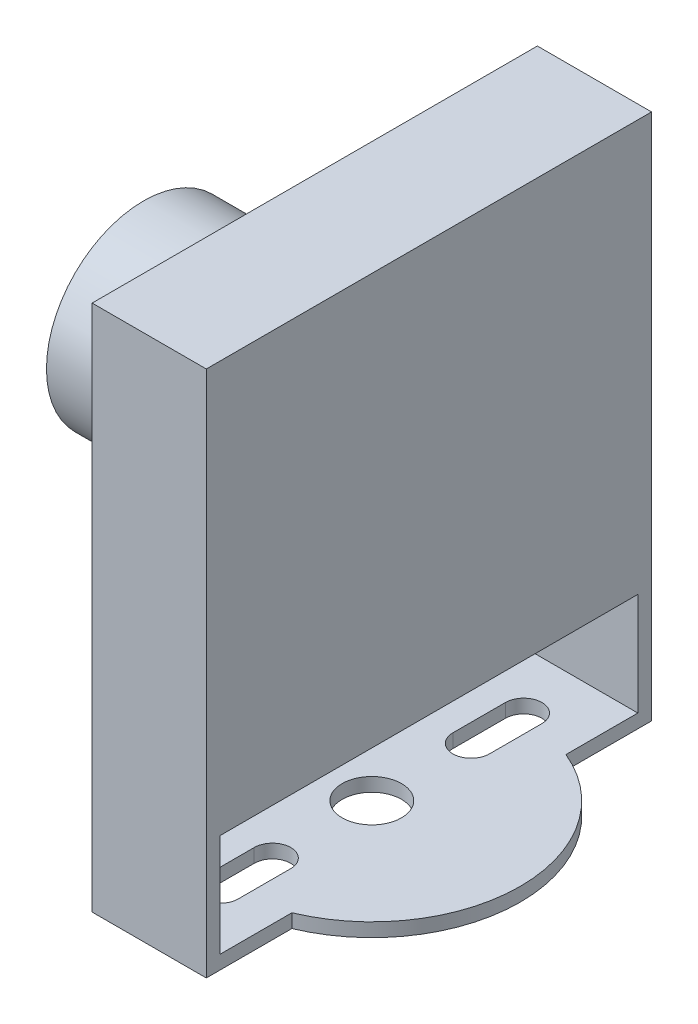
SolidWorks part; units mm, degrees
ref_plane "前视基准面" through (0, 0, 0) normal (0, 0, 1) x (1, 0, 0)
ref_plane "上视基准面" through (0, 0, 0) normal (0, 1, 0) x (1, 0, 0)
ref_plane "右视基准面" through (0, 0, 0) normal (1, 0, 0) x (0, 0, -1)
other "Configuration Table"
sketch "草图1" plane through (0, 0, 0) normal (0, 1, 0) x (1, 0, 0)
  circle A0 centre (0, 0) radius 13
  dimension "D1" = 26
extrude "凸台-拉伸1" add sketch "草图1" along normal blind 1.2
sketch "草图2" plane through (0, 1.2, 0) normal (0, 1, 0) x (1, 0, 0)
  line L1 (-5, -19.5) -> (5, -19.5)
  line L2 (-5, -19.5) -> (-5, 19.5)
  line L3 (-5, 19.5) -> (5, 19.5)
  line L4 (5, -19.5) -> (5, 19.5)
  line L5 (-5, -19.5) -> (5, 19.5) construction
  line L6 (-5, 19.5) -> (5, -19.5) construction
  point P0 (0, 0)
  dimension "D1" = 39
  dimension "D2" = 10
extrude "凸台-拉伸2" add sketch "草图2" against normal blind 1.2
sketch "草图3" plane through (0, 1.2, 0) normal (0, 1, 0) x (1, 0, 0)
  line L0 (5, 12) -> (5, 19.5) construction
  line L1 (-5, 19.5) -> (5, 19.5)
  line L2 (-5, 19.5) -> (-5, 18.3)
  line L3 (-5, 18.3) -> (5, 18.3)
  line L4 (5, 19.5) -> (5, 18.3)
  dimension "D1" = 1.2
extrude "凸台-拉伸3" add sketch "草图3" along normal blind 45
mirror "镜向1" about plane through (0, 0, 0) normal (0, 0, 1) of "凸台-拉伸3"
sketch "草图4" plane through (0, 0, -18.3) normal (0, 0, 1) x (1, 0, 0)
  line L0 (5, 0) -> (5, 46.2) construction
  line L1 (-5, 46.2) -> (5, 46.2)
  line L2 (-5, 46.2) -> (-5, 10.2)
  line L3 (-5, 10.2) -> (5, 10.2)
  line L4 (5, 46.2) -> (5, 10.2)
  dimension "D1" = 36
extrude "凸台-拉伸4" add sketch "草图4" along normal up to surface (36.6 mm away) up to face at (0, 23.7, 18.3)
sketch "草图5" plane through (-5, 0, 0) normal (-1, 0, 0) x (0, 0, 1)
  line L0 (0, 46.2) -> (0, 10.2) construction
  line L1 (-19.5, 46.2) -> (19.5, 46.2) construction
  line L2 (18.3, 10.2) -> (-18.3, 10.2) construction
  line L4 (-12.5, 15.7) -> (12.5, 15.7)
  line L5 (-12.5, 15.7) -> (-12.5, 40.7)
  line L6 (-12.5, 40.7) -> (12.5, 40.7)
  line L7 (12.5, 15.7) -> (12.5, 40.7)
  line L8 (-12.5, 15.7) -> (12.5, 40.7) construction
  line L9 (-12.5, 40.7) -> (12.5, 15.7) construction
  point P6 (0, 28.2)
  dimension "D1" = 25
extrude "凸台-拉伸5" add sketch "草图5" along normal blind 3
sketch "草图6" plane through (-8, 0, 0) normal (-1, 0, 0) x (0, 0, 1)
  line L0 (-12.5, 28.2) -> (12.5, 28.2) construction
  line L1 (-12.5, 40.7) -> (-12.5, 15.7) construction
  line L2 (12.5, 15.7) -> (12.5, 40.7) construction
  circle A0 centre (0, 28.2) radius 8.5
  dimension "D1" = 17
extrude "凸台-拉伸6" add sketch "草图6" along normal blind 12
sketch "草图7" plane through (0, 0, 0) normal (0, -1, 0) x (1, 0, 0)
  line L0 (0, 8.7) -> (0, 13.3) construction
  line L1 (-1.6, 8.7) -> (-1.6, 13.3)
  line L2 (1.6, 8.7) -> (1.6, 13.3)
  line L3 (0, 0) -> (13, 0) construction
  line L4 (0, -8.7) -> (0, -13.3) construction
  line L5 (-1.6, -8.7) -> (-1.6, -13.3)
  line L6 (1.6, -8.7) -> (1.6, -13.3)
  circle A0 centre (0, 0) radius 2.6
  arc A1 (-1.6, 8.7) -> (1.6, 8.7) centre (0, 8.7) ccw
  arc A2 (1.6, 13.3) -> (-1.6, 13.3) centre (0, 13.3) ccw
  arc A3 (5, -12) -> (5, 12) centre (0, 0) ccw construction
  arc A4 (-1.6, -8.7) -> (1.6, -8.7) centre (0, -8.7) cw
  arc A5 (1.6, -13.3) -> (-1.6, -13.3) centre (0, -13.3) cw
  point P5 (0, 11)
  point P16 (0, -11)
  dimension "D1" = 5.2
  dimension "D4" = 1.6
  dimension "D2" = 4.6
  dimension "D3" = 11
extrude "切除-拉伸1" cut sketch "草图7" against normal up to next
